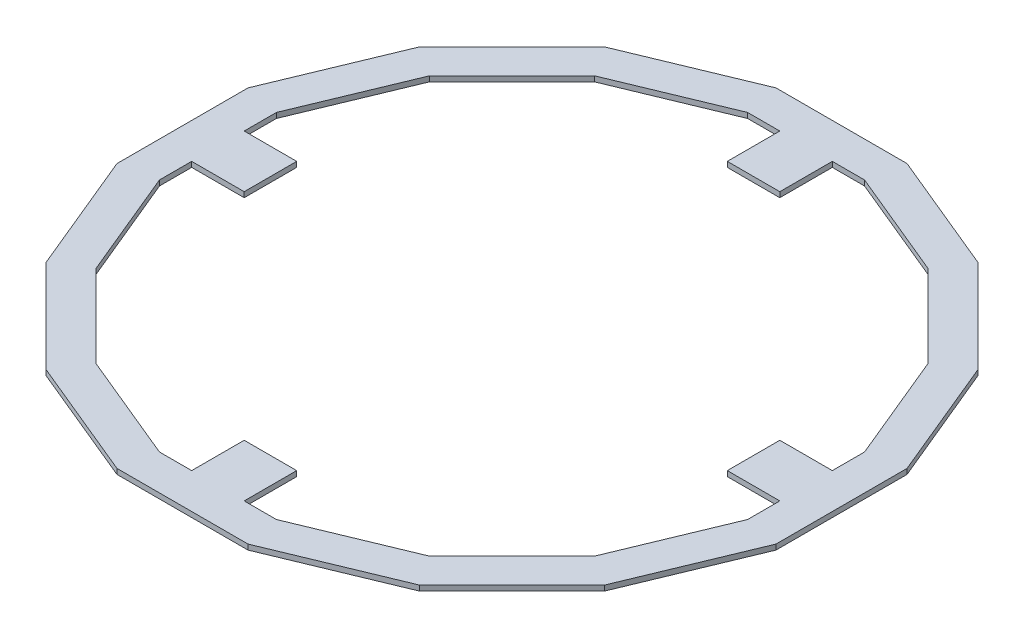
SolidWorks part; units mm, degrees
ref_plane "Front Plane" through (0, 0, 0) normal (0, 0, 1) x (1, 0, 0)
ref_plane "Top Plane" through (0, 0, 0) normal (0, 1, 0) x (1, 0, 0)
ref_plane "Right Plane" through (0, 0, 0) normal (1, 0, 0) x (0, 0, -1)
sketch "Sketch1" plane through (0, 0, 0) normal (0, 1, 0) x (1, 0, 0)
  line L1 (56, -11.1391) -> (56, 11.1391)
  line L2 (56, 11.1391) -> (47.4745, 31.7215)
  line L3 (47.4745, 31.7215) -> (31.7215, 47.4745)
  line L4 (31.7215, 47.4745) -> (11.1391, 56)
  line L5 (11.1391, 56) -> (-11.1391, 56)
  line L6 (-11.1391, 56) -> (-31.7215, 47.4745)
  line L7 (-31.7215, 47.4745) -> (-47.4745, 31.7215)
  line L8 (-47.4745, 31.7215) -> (-56, 11.1391)
  line L9 (-56, 11.1391) -> (-56, -11.1391)
  line L10 (-56, -11.1391) -> (-47.4745, -31.7215)
  line L11 (-47.4745, -31.7215) -> (-31.7215, -47.4745)
  line L12 (-31.7215, -47.4745) -> (-11.1391, -56)
  line L13 (-11.1391, -56) -> (11.1391, -56)
  line L14 (11.1391, -56) -> (31.7215, -47.4745)
  line L15 (31.7215, -47.4745) -> (47.4745, -31.7215)
  line L16 (47.4745, -31.7215) -> (56, -11.1391)
  line L17 (62.75, -12.4818) -> (62.75, 12.4818)
  line L18 (62.75, 12.4818) -> (53.1969, 35.545)
  line L19 (53.1969, 35.545) -> (35.545, 53.1969)
  line L20 (35.545, 53.1969) -> (12.4818, 62.75)
  line L21 (12.4818, 62.75) -> (-12.4818, 62.75)
  line L22 (-12.4818, 62.75) -> (-35.545, 53.1969)
  line L23 (-35.545, 53.1969) -> (-53.1969, 35.545)
  line L24 (-53.1969, 35.545) -> (-62.75, 12.4818)
  line L25 (-62.75, 12.4818) -> (-62.75, -12.4818)
  line L26 (-62.75, -12.4818) -> (-53.1969, -35.545)
  line L27 (-53.1969, -35.545) -> (-35.545, -53.1969)
  line L28 (-35.545, -53.1969) -> (-12.4818, -62.75)
  line L29 (-12.4818, -62.75) -> (12.4818, -62.75)
  line L30 (12.4818, -62.75) -> (35.545, -53.1969)
  line L31 (35.545, -53.1969) -> (53.1969, -35.545)
  line L32 (53.1969, -35.545) -> (62.75, -12.4818)
  circle A0 centre (0, 0) radius 56 construction
  circle A1 centre (0, 0) radius 62.75 construction
  dimension "D1" = 112
  dimension "D2" = 125.5
extrude "Boss-Extrude1" add sketch "Sketch1" along normal blind 1
sketch "Sketch2" plane through (0, 1, 0) normal (0, 1, 0) x (1, 0, 0)
  line L0 (-11.1391, -56) -> (11.1391, -56) construction
  line L1 (-5, -56) -> (5, -56)
  line L2 (-5, -56) -> (-5, -46)
  line L3 (-5, -46) -> (5, -46)
  line L4 (5, -56) -> (5, -46)
  line L5 (-56, 5) -> (-46, 5)
  line L6 (-56, 5) -> (-56, -5)
  line L7 (-56, -5) -> (-46, -5)
  line L8 (-46, 5) -> (-46, -5)
  line L9 (5, 56) -> (5, 46)
  line L10 (5, 56) -> (-5, 56)
  line L11 (-5, 56) -> (-5, 46)
  line L12 (5, 46) -> (-5, 46)
  line L13 (56, -5) -> (46, -5)
  line L14 (56, -5) -> (56, 5)
  line L15 (56, 5) -> (46, 5)
  line L16 (46, -5) -> (46, 5)
  point P6 (0, -46)
  point P8 (0, 0)
  point P22 (0, 0)
  dimension "D1" = 10
  dimension "D2" = 10
  dimension "D3" = 4
extrude "Boss-Extrude2" add sketch "Sketch2" against normal up to surface (1 mm away) up to face at (0, 0, 0)
